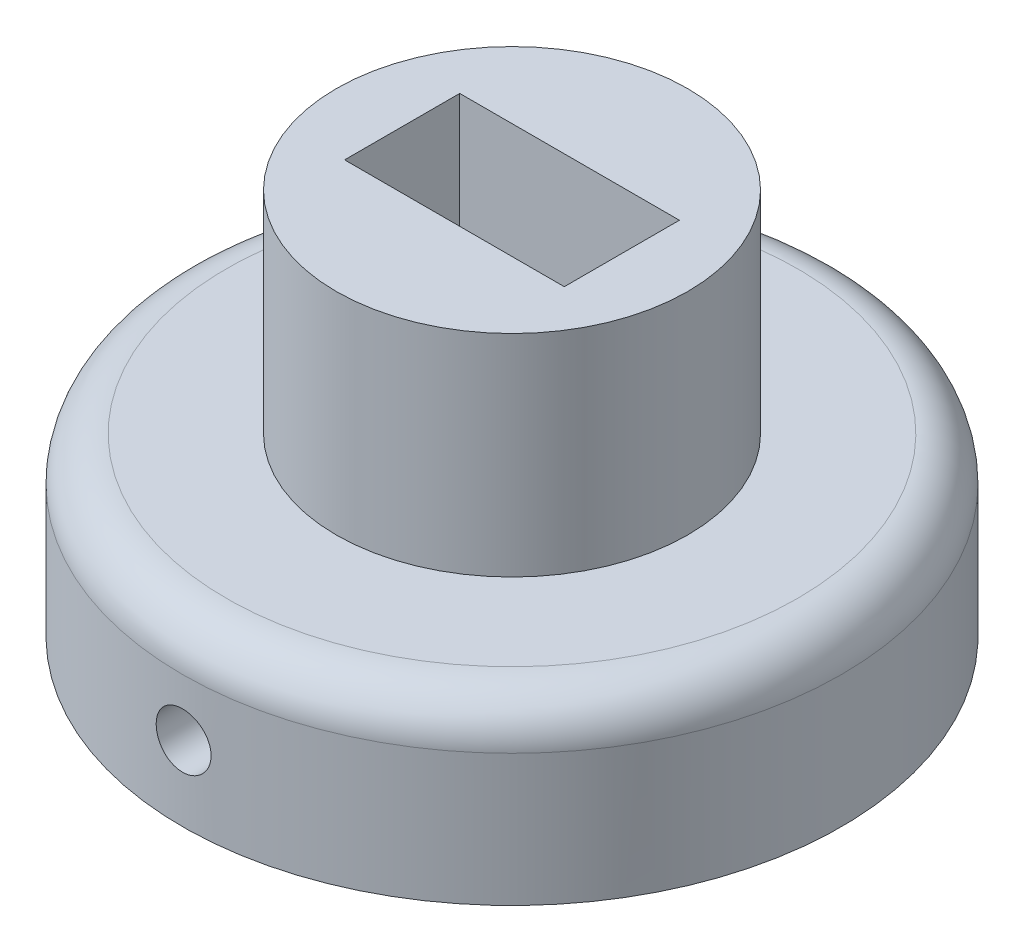
SolidWorks part; units mm, degrees
ref_plane "Front Plane" through (0, 0, 0) normal (0, 0, 1) x (1, 0, 0)
ref_plane "Top Plane" through (0, 0, 0) normal (0, 1, 0) x (1, 0, 0)
ref_plane "Right Plane" through (0, 0, 0) normal (1, 0, 0) x (0, 0, -1)
sketch "Sketch2" plane through (0, 0, 0) normal (0, 0, 1) x (1, 0, 0)
  line L0 (9.525, 0) -> (9.525, 5.08)
  line L1 (9.525, 5.08) -> (5.08, 5.08)
  line L2 (5.08, 5.08) -> (5.08, 11.176)
  line L3 (5.08, 11.176) -> (0, 11.176)
  line L4 (0, 11.176) -> (0, 0) construction
  line L5 (0, 0) -> (9.525, 0)
  line L6 (0, 11.176) -> (0, 0)
  dimension "D1" = 5.08
  dimension "D2" = 9.525
  dimension "D3" = 11.176
  dimension "D4" = 5.08
revolve "Revolve1" add sketch "Sketch2" angle 360 about L4
sketch "Sketch3" plane through (0, 0, 0) normal (0, -1, 0) x (1, 0, 0)
  line L1 (6.4525, 0) -> (3.2262, 5.588)
  line L2 (3.2262, 5.588) -> (-3.2262, 5.588)
  line L3 (-3.2262, 5.588) -> (-6.4525, 0)
  line L4 (-6.4525, 0) -> (-3.2262, -5.588)
  line L5 (-3.2262, -5.588) -> (3.2262, -5.588)
  line L6 (3.2262, -5.588) -> (6.4525, 0)
  circle A0 centre (0, 0) radius 5.588 construction
  dimension "D1" = 11.176
extrude "Cut-Extrude1" cut sketch "Sketch3" against normal blind 4.318
sketch "Sketch4" plane through (0, 11.176, 0) normal (0, 1, 0) x (1, 0, 0)
  line L1 (-3.175, -1.6637) -> (3.175, -1.6637)
  line L2 (-3.175, -1.6637) -> (-3.175, 1.6637)
  line L3 (-3.175, 1.6637) -> (3.175, 1.6637)
  line L4 (3.175, -1.6637) -> (3.175, 1.6637)
  line L5 (-3.175, -1.6637) -> (3.175, 1.6637) construction
  line L6 (-3.175, 1.6637) -> (3.175, -1.6637) construction
  point P0 (0, 0)
  dimension "D1" = 6.35
  dimension "D2" = 3.3274
extrude "Cut-Extrude2" cut sketch "Sketch4" against normal blind 7.112
sketch "Sketch5" plane through (0, 0, -5.588) normal (0, 0, 1) x (1, 0, 0)
  line L4 (-3.2262, 0) -> (3.2262, 0)
  line L5 (3.2262, 0) -> (3.2262, 4.318)
  line L6 (3.2262, 4.318) -> (-3.2262, 4.318)
  line L7 (-3.2262, 4.318) -> (-3.2262, 0)
  line L8 (-3.2262, 0) -> (3.2262, 0) construction
  line L9 (3.2262, 0) -> (3.2262, 4.318) construction
  line L10 (3.2262, 4.318) -> (-3.2262, 4.318) construction
  line L11 (-3.2262, 4.318) -> (-3.2262, 0) construction
  circle A0 centre (0, 2.159) radius 0.7938
  point P6 (0, 0)
  point P7 (-3.2262, 2.159)
  point P8 (0, 4.318)
  dimension "D2" = 1.5875
  dimension "D1" = 0
extrude "Cut-Extrude3" cut sketch "Sketch5" against normal through all both and the other way through all
fillet "Fillet2" radius 1.27 1 edges at (-9.525, 5.08, 0)
